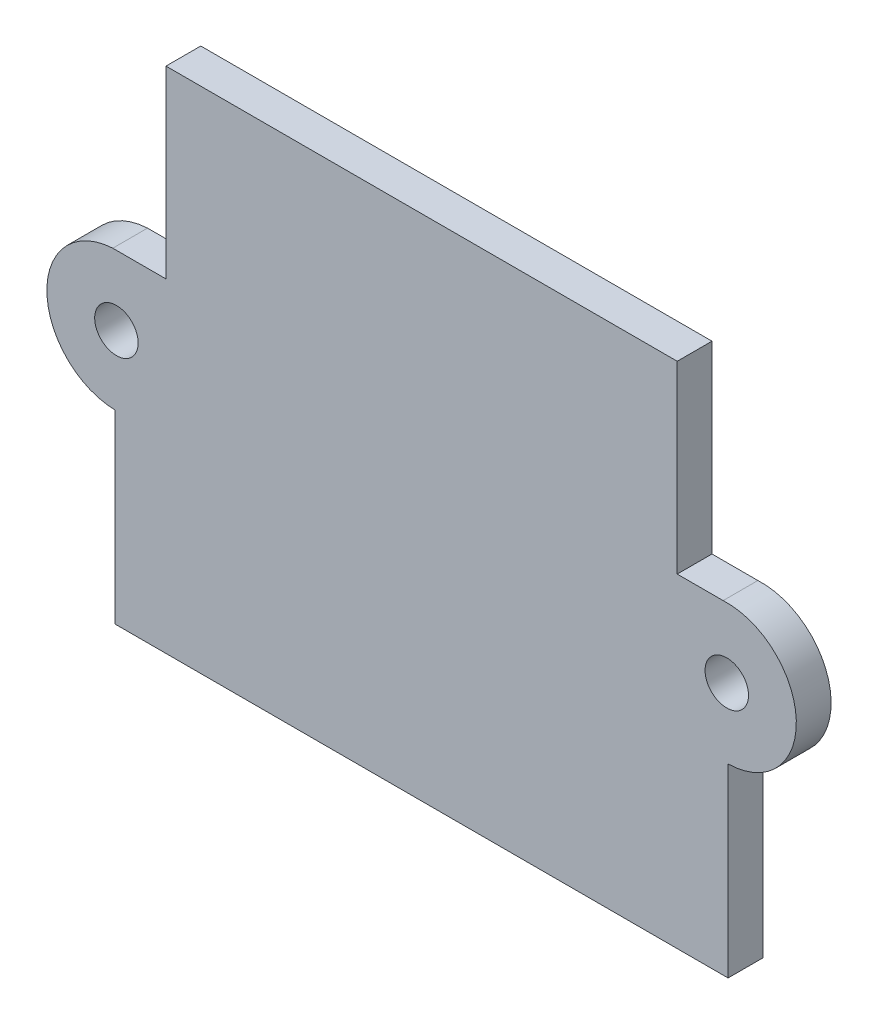
SolidWorks part; units mm, degrees
ref_plane "Front Plane" through (0, 0, 0) normal (0, 0, 1) x (1, 0, 0)
ref_plane "Top Plane" through (0, 0, 0) normal (0, 1, 0) x (1, 0, 0)
ref_plane "Right Plane" through (0, 0, 0) normal (1, 0, 0) x (0, 0, -1)
sketch "Sketch1" plane through (0, 0, 0) normal (0, 0, 1) x (1, 0, 0)
  line L0 (0, 7.4306) -> (0, -7.4306) construction
  line L1 (-7.4676, 7.4306) -> (7.4676, 7.4306)
  line L2 (-7.4676, 7.4306) -> (-7.4676, 2.0458)
  line L3 (-8.9535, -7.4306) -> (8.9535, -7.4306)
  line L4 (7.4676, 7.4306) -> (7.4676, 2.0458)
  line L5 (8.9535, -2.0151) -> (8.9535, -7.4306)
  line L6 (7.4676, 2.0458) -> (8.8086, 2.0458)
  line L7 (-8.9535, -2.0151) -> (-8.9535, -7.4306)
  line L10 (-7.4676, 2.0458) -> (-9.0222, 2.0458)
  arc A0 (8.9535, -2.0151) -> (8.8086, 2.0458) centre (8.9154, 0.0166) ccw
  arc A1 (-9.0222, 2.0458) -> (-8.9535, -2.0151) centre (-8.9154, 0.0166) ccw
  circle A2 centre (-8.9154, 0.0166) radius 0.635
  circle A3 centre (8.9154, 0.0166) radius 0.635
  point P8 (0, 0)
  dimension "D7" = 17.8308
  dimension "D9" = 2.032
  dimension "D10" = 2.032
  dimension "D12" = 1.27
  dimension "D13" = 1.27
  dimension "D4" = 7.4471
  dimension "D1" = 14.9352
  dimension "D2" = 14.9352
  dimension "D3" = 5.3848
  dimension "D5" = 5.3848
  dimension "D8" = 1.4478
  dimension "D11" = 1.4478
  dimension "D14" = 17.907
extrude "Boss-Extrude1" add sketch "Sketch1" along normal blind 1.016 contours L4 L6 A0 L5 L3 L7 A1 L10 L2 L1 | A2 | A3
